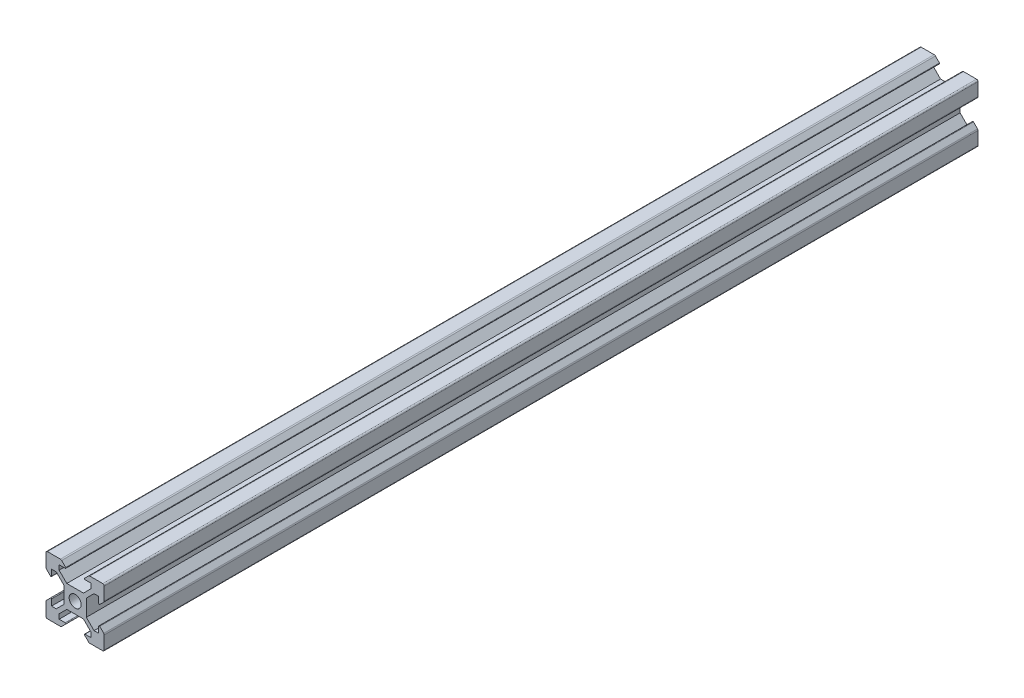
SolidWorks part; units mm, degrees
material "6063-T5"
ref_plane "Front Plane" through (0, 0, 0) normal (1, 0, 0) x (0, 1, 0)
ref_plane "Top Plane" through (0, 0, 0) normal (0, 0, 1) x (0, 1, 0)
ref_plane "Right Plane" through (0, 0, 0) normal (0, 1, 0) x (-1, 0, 0)
sketch "Sketch1" plane through (0, 0, 0) normal (0, 0, 1) x (0, 1, 0)
  line L0 (0, 0) -> (-10, 10) construction
  line L5 (-2.8601, -3.85) -> (2.8601, -3.85)
  line L6 (-3.85, -2.8601) -> (-3.85, 2.8601)
  line L11 (-2.8601, 3.85) -> (2.8601, 3.85)
  line L12 (3.85, -2.8601) -> (3.85, 2.8601)
  line L15 (-9.5, 10) -> (-5.0485, 10)
  line L16 (-4.6243, 9.8243) -> (-3.2414, 8.4414)
  line L17 (-3.3828, 8.1) -> (-5.5, 8.1)
  line L18 (-5.5, 8.1) -> (-5.5, 6.4899)
  line L19 (-5.5, 6.4899) -> (-2.8601, 3.85)
  line L20 (-6.4899, 5.5) -> (-3.85, 2.8601)
  line L21 (-10, 9.5) -> (-10, 5.0485)
  line L22 (-8.1, 5.5) -> (-6.4899, 5.5)
  line L23 (-8.1, 3.3828) -> (-8.1, 5.5)
  line L24 (-9.8243, 4.6243) -> (-8.4414, 3.2414)
  line L25 (10, 9.5) -> (10, 5.0485)
  line L26 (9.8243, 4.6243) -> (8.4414, 3.2414)
  line L27 (8.1, 3.3828) -> (8.1, 5.5)
  line L28 (8.1, 5.5) -> (6.4899, 5.5)
  line L29 (6.4899, 5.5) -> (3.85, 2.8601)
  line L30 (5.5, 6.4899) -> (2.8601, 3.85)
  line L31 (9.5, 10) -> (5.0485, 10)
  line L32 (5.5, 8.1) -> (5.5, 6.4899)
  line L33 (3.3828, 8.1) -> (5.5, 8.1)
  line L34 (4.6243, 9.8243) -> (3.2414, 8.4414)
  line L35 (9.5, -10) -> (5.0485, -10)
  line L36 (4.6243, -9.8243) -> (3.2414, -8.4414)
  line L37 (3.3828, -8.1) -> (5.5, -8.1)
  line L38 (5.5, -8.1) -> (5.5, -6.4899)
  line L39 (5.5, -6.4899) -> (2.8601, -3.85)
  line L40 (6.4899, -5.5) -> (3.85, -2.8601)
  line L41 (10, -9.5) -> (10, -5.0485)
  line L42 (8.1, -5.5) -> (6.4899, -5.5)
  line L43 (8.1, -3.3828) -> (8.1, -5.5)
  line L44 (9.8243, -4.6243) -> (8.4414, -3.2414)
  line L45 (-10, -9.5) -> (-10, -5.0485)
  line L46 (-9.8243, -4.6243) -> (-8.4414, -3.2414)
  line L47 (-8.1, -3.3828) -> (-8.1, -5.5)
  line L48 (-8.1, -5.5) -> (-6.4899, -5.5)
  line L49 (-6.4899, -5.5) -> (-3.85, -2.8601)
  line L50 (-5.5, -6.4899) -> (-2.8601, -3.85)
  line L51 (-9.5, -10) -> (-5.0485, -10)
  line L52 (-5.5, -8.1) -> (-5.5, -6.4899)
  line L53 (-3.3828, -8.1) -> (-5.5, -8.1)
  line L54 (-4.6243, -9.8243) -> (-3.2414, -8.4414)
  circle A1 centre (0, 0) radius 2.05
  arc A2 (-10, -9.5) -> (-9.5, -10) centre (-9.5, -9.5) ccw
  arc A3 (9.5, -10) -> (10, -9.5) centre (9.5, -9.5) ccw
  arc A4 (10, 9.5) -> (9.5, 10) centre (9.5, 9.5) ccw
  arc A5 (-10, 9.5) -> (-9.5, 10) centre (-9.5, 9.5) cw
  arc A6 (-3.2414, 8.4414) -> (-3.3828, 8.1) centre (-3.3828, 8.3) cw
  arc A7 (3.3828, 8.1) -> (3.2414, 8.4414) centre (3.3828, 8.3) cw
  arc A8 (8.4414, 3.2414) -> (8.1, 3.3828) centre (8.3, 3.3828) cw
  arc A9 (8.1, -3.3828) -> (8.4414, -3.2414) centre (8.3, -3.3828) cw
  arc A10 (3.2414, -8.4414) -> (3.3828, -8.1) centre (3.3828, -8.3) cw
  arc A11 (-3.3828, -8.1) -> (-3.2414, -8.4414) centre (-3.3828, -8.3) cw
  arc A12 (-8.4414, -3.2414) -> (-8.1, -3.3828) centre (-8.3, -3.3828) cw
  arc A13 (-8.1, 3.3828) -> (-8.4414, 3.2414) centre (-8.3, 3.3828) cw
  arc A14 (5.0485, 10) -> (4.6243, 9.8243) centre (5.0485, 9.4) ccw
  arc A15 (10, 5.0485) -> (9.8243, 4.6243) centre (9.4, 5.0485) cw
  arc A16 (10, -5.0485) -> (9.8243, -4.6243) centre (9.4, -5.0485) ccw
  arc A17 (5.0485, -10) -> (4.6243, -9.8243) centre (5.0485, -9.4) cw
  arc A18 (-5.0485, -10) -> (-4.6243, -9.8243) centre (-5.0485, -9.4) ccw
  arc A19 (-10, -5.0485) -> (-9.8243, -4.6243) centre (-9.4, -5.0485) cw
  arc A20 (-5.0485, 10) -> (-4.6243, 9.8243) centre (-5.0485, 9.4) cw
  arc A21 (-10, 5.0485) -> (-9.8243, 4.6243) centre (-9.4, 5.0485) ccw
  point P0 (0, 0)
  point P56 (0, 0)
  point P64 (-2.9, 8.1)
  point P79 (-8.1, 2.9)
  point P94 (-4.8, 10)
  point P97 (-10, 4.8)
  dimension "D3" = 7.7
  dimension "D2" = 4.1
  dimension "D9" = 0.5
  dimension "D10" = 0.2
  dimension "D11" = 0.6
  dimension "D1" = 10
  dimension "D4" = 7.1
  dimension "D5" = 1.4
  dimension "D6" = 4.5
  dimension "D7" = 1.9
  dimension "D8" = 4
extrude "Boss-Extrude1" add sketch "Sketch1" along normal blind 300
ref_plane "Midplane" through (0, 0, 150) normal (0, 0, -1) x (0, 1, 0)
